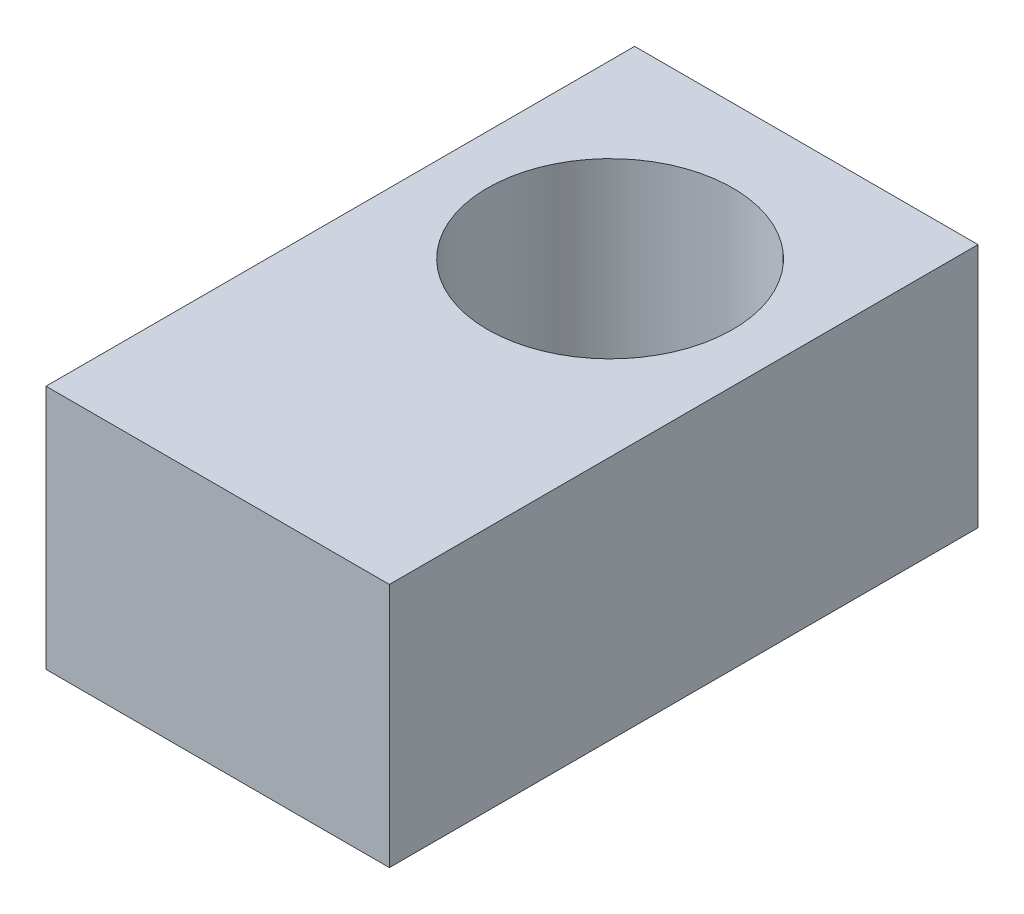
SolidWorks part; units mm, degrees
ref_plane "Front Plane" through (0, 0, 0) normal (0, 0, 1) x (1, 0, 0)
ref_plane "Top Plane" through (0, 0, 0) normal (0, 1, 0) x (1, 0, 0)
ref_plane "Right Plane" through (0, 0, 0) normal (1, 0, 0) x (0, 0, -1)
sketch "Sketch1" plane through (0, 0, 0) normal (0, 1, 0) x (1, 0, 0)
  line L1 (-3.5, 6) -> (3.5, 6)
  line L2 (-3.5, 6) -> (-3.5, -6)
  line L3 (-3.5, -6) -> (3.5, -6)
  line L4 (3.5, 6) -> (3.5, -6)
  line L5 (-3.5, 6) -> (3.5, -6) construction
  line L6 (-3.5, -6) -> (3.5, 6) construction
  point P0 (0, 0)
  dimension "D1" = 7
  dimension "D2" = 12
extrude "Boss-Extrude1" add sketch "Sketch1" along normal blind 5
sketch "Sketch2" plane through (0, 5, 0) normal (0, 1, 0) x (1, 0, 0)
  circle A0 centre (0, 2) radius 2.5
  point P2 (0, 0)
  point P3 (2.5937, -1.5598)
  dimension "D1" = 5
  dimension "D2" = 2
extrude "Cut-Extrude1" cut sketch "Sketch2" against normal up to next
